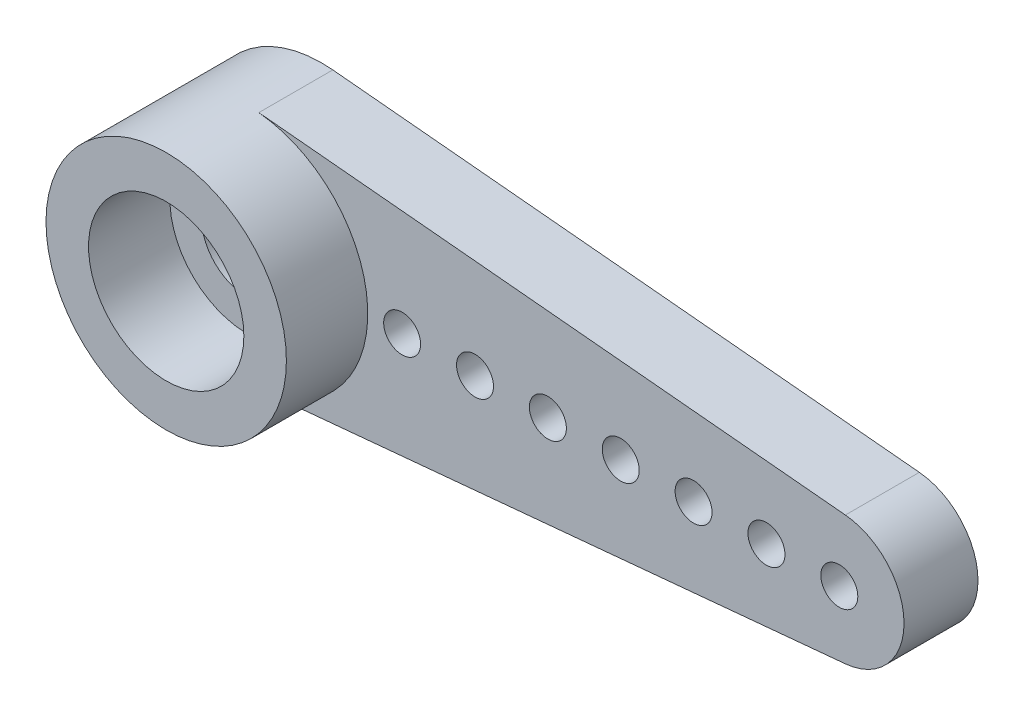
SolidWorks part; units mm, degrees
ref_plane "Plano frontal" through (0, 0, 0) normal (0, 0, 1) x (1, 0, 0)
ref_plane "Plano superior" through (0, 0, 0) normal (0, 1, 0) x (1, 0, 0)
ref_plane "Plano direito" through (0, 0, 0) normal (1, 0, 0) x (0, 0, -1)
sketch "Esboço1" plane through (0, 0, 0) normal (0, 0, 1) x (1, 0, 0)
  line L0 (16.1641, 1.7423) -> (0.3047, 3.2357)
  line L1 (0.3047, -3.2357) -> (16.1641, -1.7423)
  arc A0 (0.3047, 3.2357) -> (0.3047, -3.2357) centre (0, 0) ccw
  arc A1 (16.1641, -1.7423) -> (16.1641, 1.7423) centre (16, 0) ccw
  circle A2 centre (0, 0) radius 1.25
  circle A3 centre (16, 0) radius 0.5
  circle A4 centre (14.03, 0) radius 0.5
  circle A5 centre (12.06, 0) radius 0.5
  circle A6 centre (10.09, 0) radius 0.5
  circle A7 centre (8.12, 0) radius 0.5
  circle A8 centre (6.15, 0) radius 0.5
  circle A9 centre (4.18, 0) radius 0.5
  point P10 (0, 0)
  dimension "D1" = 3.5
  dimension "D2" = 6.5
  dimension "D4" = 2.5
  dimension "D5" = 1
  dimension "D3" = 16
  dimension "D6" = 7
extrude "Ressalto-extrusão1" add sketch "Esboço1" along normal blind 2
sketch "Esboço2" plane through (0, 0, 2) normal (0, 0, 1) x (1, 0, 0)
  circle A0 centre (0, 0) radius 3.25
  circle A1 centre (0, 0) radius 2.1
  arc A2 (0.3047, 3.2357) -> (0.3047, -3.2357) centre (0, 0) ccw construction
  dimension "D1" = 4.2
extrude "Ressalto-extrusão2" add sketch "Esboço2" along normal blind 2.2
